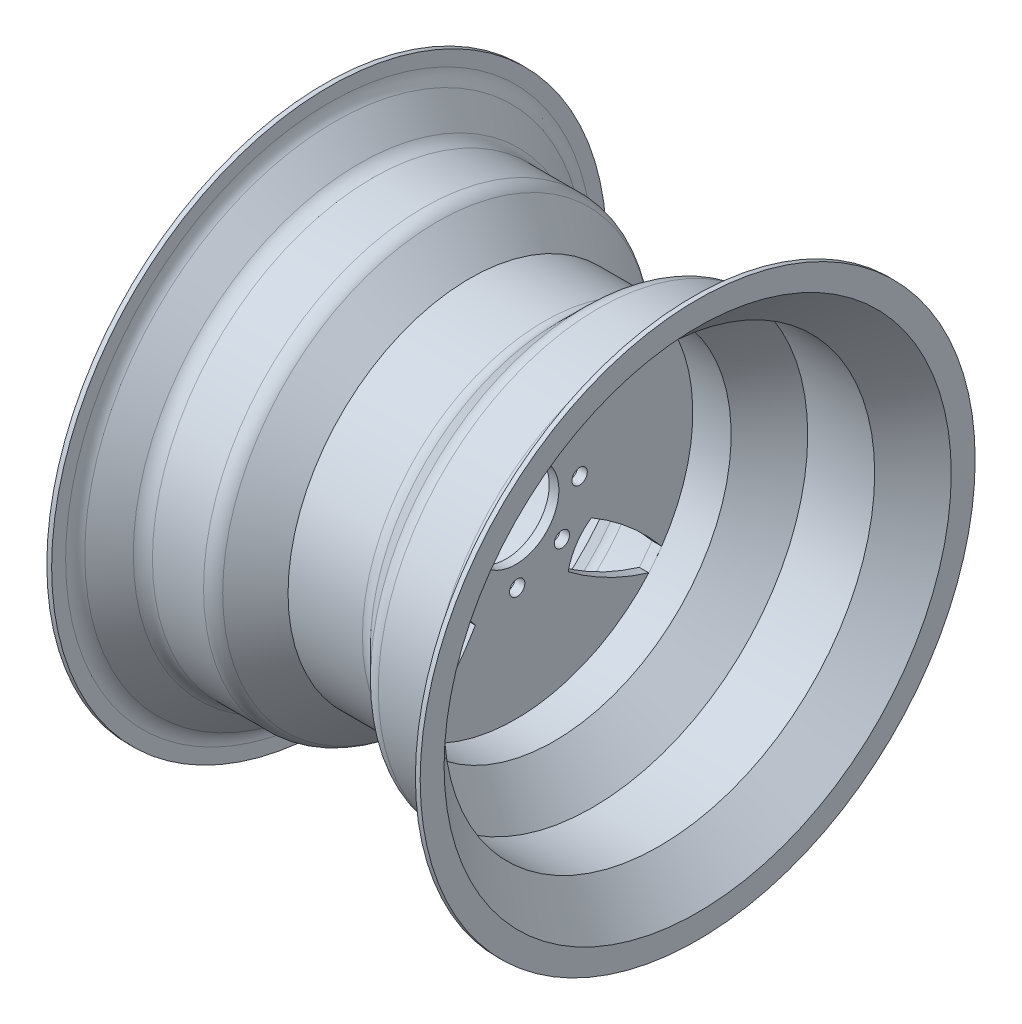
SolidWorks part; units mm, degrees
material "201 Annealed Stainless Steel (SS)"
ref_plane "Front Plane" through (0, 0, 0) normal (0, 0, 1) x (1, 0, 0)
ref_plane "Top Plane" through (0, 0, 0) normal (0, 1, 0) x (1, 0, 0)
ref_plane "Right Plane" through (0, 0, 0) normal (1, 0, 0) x (0, 0, -1)
sketch "Sketch1" plane through (0, 0, 0) normal (0, 0, 1) x (1, 0, 0)
  line L0 (-343.891, 0) -> (0, 0) construction
  line L1 (0, 0) -> (0, 235.0746) construction
  line L2 (-195.0729, 290) -> (-195.0729, 265)
  line L3 (-195.0729, 265) -> (-155.0729, 225)
  line L4 (-155.0729, 225) -> (-85.0729, 225)
  line L5 (-85.0729, 225) -> (-45.0729, 185)
  line L6 (-45.0729, 185) -> (-5, 185)
  line L7 (85.0729, 225) -> (45.0729, 185)
  line L8 (155.0729, 225) -> (85.0729, 225)
  line L9 (195.0729, 265) -> (155.0729, 225)
  line L10 (195.0729, 290) -> (195.0729, 265)
  line L11 (-190.0729, 290) -> (-190.0729, 267.0711)
  line L12 (-190.0729, 267.0711) -> (-153.0018, 230)
  line L13 (-153.0018, 230) -> (-83.0018, 230)
  line L14 (-83.0018, 230) -> (-43.0018, 190)
  line L15 (-43.0018, 190) -> (43.0018, 190)
  line L16 (83.0018, 230) -> (43.0018, 190)
  line L17 (153.0018, 230) -> (83.0018, 230)
  line L18 (190.0729, 267.0711) -> (153.0018, 230)
  line L19 (190.0729, 290) -> (190.0729, 267.0711)
  line L20 (-195.0729, 290) -> (-190.0729, 290)
  line L21 (190.0729, 290) -> (195.0729, 290)
  line L22 (5, 185) -> (45.0729, 185)
  line L24 (-5, 185) -> (-5, 45)
  line L25 (-5, 45) -> (5, 45)
  line L26 (5, 185) -> (5, 45)
  line L27 (-45.0729, 185) -> (45.0729, 185) construction
  point P11 (0, 163.3566)
  point P29 (-53.9024, 315)
  point P30 (-50.5709, 295)
  point P31 (-163.2838, 315)
  point P32 (31.6307, 280)
  point P33 (-46.3442, 275)
  point P34 (49.7131, 280)
  point P35 (-73.0018, 335)
  dimension "D1" = 290
  dimension "D2" = 25
  dimension "D3" = 40
  dimension "D4" = 70
  dimension "D5" = 40
  dimension "D6" = 50
  dimension "D7" = 135
  dimension "D8" = 135
  dimension "D10" = 10
  dimension "D11" = 5
  dimension "D12" = 45
  dimension "D9" = 5
revolve "Revolve1" add sketch "Sketch1" angle 360 about L0
fillet "Fillet1" radius 20 8 edges at (-190.0729, 0, 267.0711) (-153.0018, 0, 230) (-83.0018, 0, 230) (-45.0729, 0, 185) (43.0018, 0, 190) (83.0018, 0, 230) (153.0018, 0, 230) (190.0729, 0, 267.0711)
sketch "Sketch2" plane through (-5, 0, 0) normal (-1, 0, 0) x (0, 0, 1)
  arc A0 (54.7462, 78.899) -> (78.899, 42.1969) centre (113.4413, 91.2267) ccw
  arc A1 (78.899, 42.1969) -> (152.4715, 104.7732) centre (-62.6289, 283.1337) ccw
  circle A2 centre (0, 0) radius 185 construction
  arc A3 (54.7462, 78.899) -> (139.0126, 122.0676) centre (217.6585, -135.2808) cw
  arc A4 (139.0126, 122.0676) -> (152.4715, 104.7732) centre (-118.4919, -92.2136) cw
  arc A5 (42.1969, -78.899) -> (104.7732, -152.4715) centre (283.1337, 62.6289) ccw
  arc A6 (78.899, -54.7462) -> (122.0676, -139.0126) centre (-135.2808, -217.6585) cw
  arc A7 (78.899, -54.7462) -> (42.1969, -78.899) centre (91.2267, -113.4413) ccw
  arc A8 (122.0676, -139.0126) -> (104.7732, -152.4715) centre (-92.2136, 118.4919) cw
  arc A9 (-78.899, -42.1969) -> (-152.4715, -104.7732) centre (62.6289, -283.1337) ccw
  arc A10 (-54.7462, -78.899) -> (-139.0126, -122.0676) centre (-217.6585, 135.2808) cw
  arc A11 (-54.7462, -78.899) -> (-78.899, -42.1969) centre (-113.4413, -91.2267) ccw
  arc A12 (-139.0126, -122.0676) -> (-152.4715, -104.7732) centre (118.4919, 92.2136) cw
  arc A13 (-42.1969, 78.899) -> (-104.7732, 152.4715) centre (-283.1337, -62.6289) ccw
  arc A14 (-78.899, 54.7462) -> (-122.0676, 139.0126) centre (135.2808, 217.6585) cw
  arc A15 (-78.899, 54.7462) -> (-42.1969, 78.899) centre (-91.2267, 113.4413) ccw
  arc A16 (-122.0676, 139.0126) -> (-104.7732, 152.4715) centre (92.2136, -118.4919) cw
  circle A17 centre (0, 0) radius 45 construction
  point P5 (78.899, 42.1969)
  point P9 (54.7462, 78.899)
  point P10 (135.2808, 120.545)
  point P37 (0, 0)
  point P40 (152.4715, 104.7732)
  point P41 (-109.4678, -88.2006)
  point P42 (0, 0)
  dimension "D1" = 4
extrude "Cut-Extrude2" cut sketch "Sketch2" against normal through all
sketch "Sketch3" plane through (-5, 0, 0) normal (-1, 0, 0) x (0, 0, 1)
  circle A0 centre (1.4645, 66.7352) radius 8
  circle A1 centre (48.2245, 46.1534) radius 8
  circle A2 centre (66.7352, -1.4645) radius 8
  circle A3 centre (46.1534, -48.2245) radius 8
  circle A4 centre (-1.4645, -66.7352) radius 8
  circle A5 centre (-48.2245, -46.1534) radius 8
  circle A6 centre (-66.7352, 1.4645) radius 8
  circle A7 centre (-46.1534, 48.2245) radius 8
  circle A8 centre (0, 0) radius 45 construction
  point P19 (0, 0)
  dimension "D1" = 16
  dimension "D2" = 8
extrude "Cut-Extrude3" cut sketch "Sketch3" against normal through all
